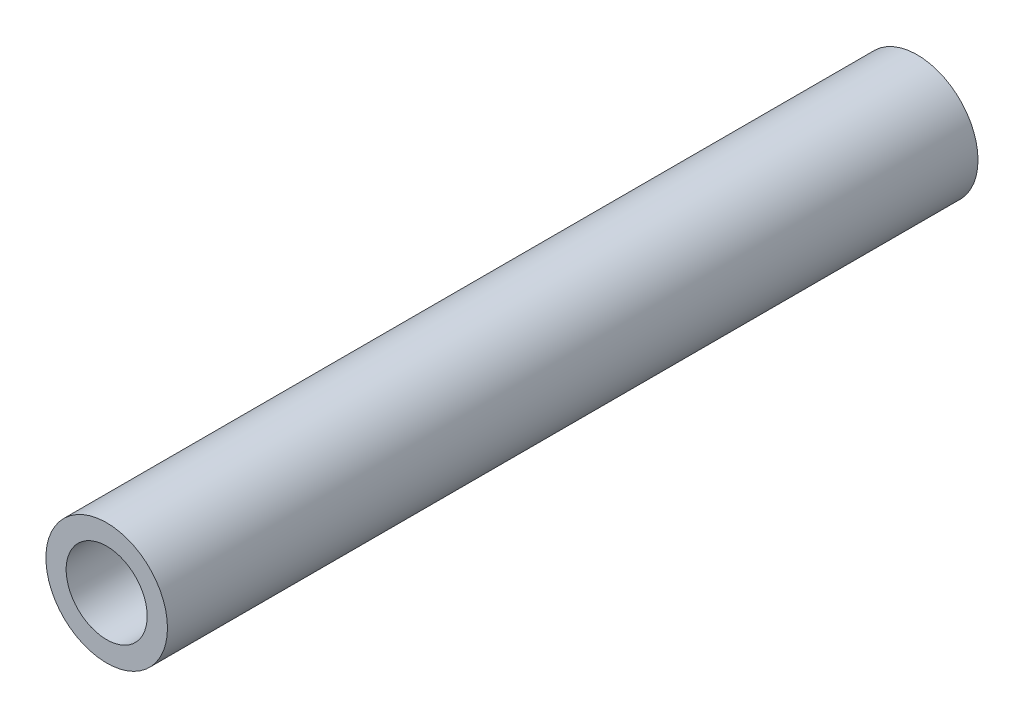
SolidWorks part; units mm, degrees
ref_plane "Přední rovina" through (0, 0, 0) normal (0, 0, 1) x (1, 0, 0)
ref_plane "Vrchní rovina" through (0, 0, 0) normal (0, 1, 0) x (1, 0, 0)
ref_plane "Pravá rovina" through (0, 0, 0) normal (1, 0, 0) x (0, 0, -1)
sketch "Skica1" plane through (0, 0, 0) normal (0, 0, 1) x (1, 0, 0)
  circle A0 centre (0, 0) radius 3
  dimension "d" = 6
extrude "Vysunout1" add sketch "Skica1" along normal mid plane 40
hole_wizard "Díra1" positions "Skica3" profile "Skica2" legacy
sketch "Skica3" plane through (0, 0, 20) normal (0, 0, 1) x (1, 0, 0)
  circle A0 centre (0, 0) radius 3 construction
  point P0 (0, 0)
sketch "Skica2" plane through (0, 0, 20) normal (1, 0, 0) x (0, -1, 0)
  line L0 (0, 0) -> (0, 5.2017)
  line L1 (0, 5.2017) -> (2, 4)
  line L2 (2, 4) -> (2, 0)
  line L4 (2, 0) -> (0, 0)
  line L6 (0, 5.2017) -> (-2, 4) construction
  line L7 (0, -4.2442) -> (0, 117.3081) construction
  dimension "Průměr" = 4
  dimension "Hloubka" = 4
  dimension "Úhel vrtání" = 118
mirror "Zrcadlit1" about plane through (0, 0, 0) normal (0, 0, 1) of "Díra1"
